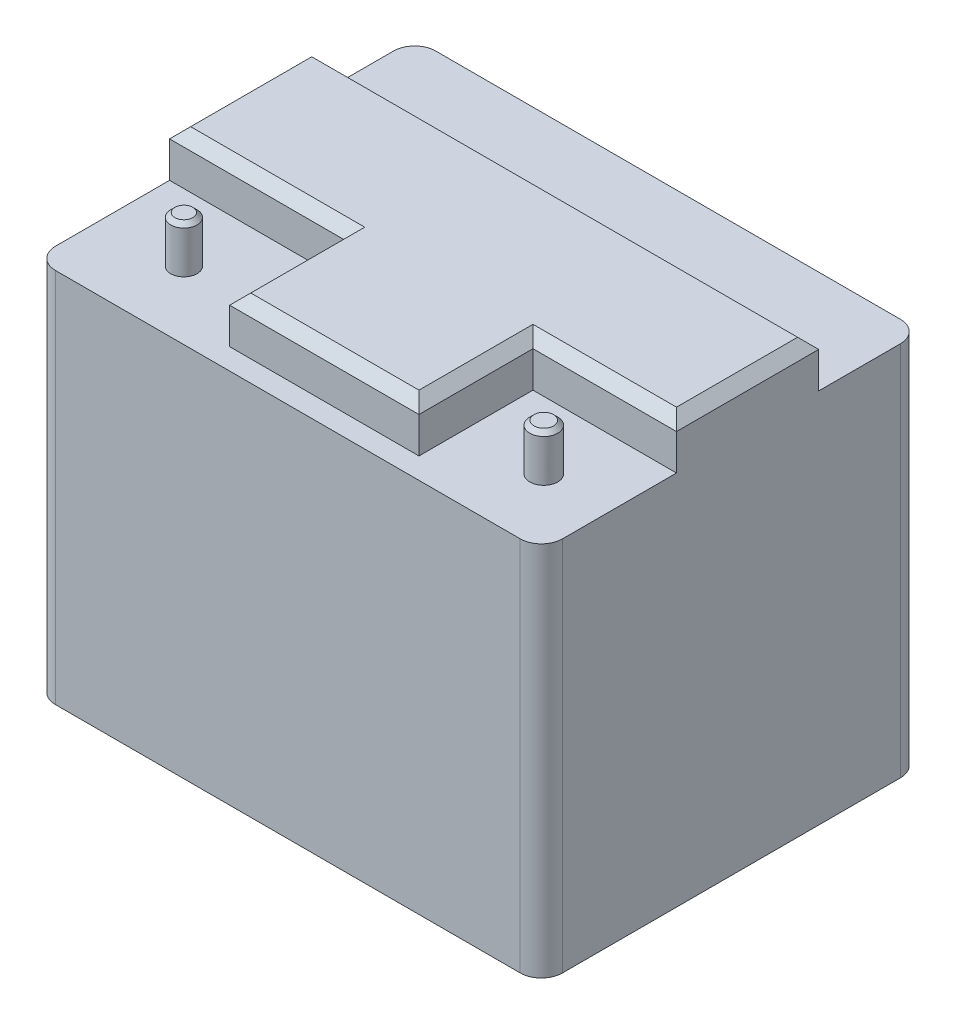
SolidWorks part; units mm, degrees
ref_plane "Alzado" through (0, 0, 0) normal (0, 0, 1) x (1, 0, 0)
ref_plane "Planta" through (0, 0, 0) normal (0, 1, 0) x (1, 0, 0)
ref_plane "Vista lateral" through (0, 0, 0) normal (1, 0, 0) x (0, 0, -1)
sketch "Croquis1" plane through (0, 0, 0) normal (0, 1, 0) x (1, 0, 0)
  line L1 (-110, 90) -> (110, 90)
  line L2 (-120, 80) -> (-120, -80)
  line L3 (-110, -90) -> (110, -90)
  line L4 (120, 80) -> (120, -80)
  line L5 (-120, 90) -> (120, -90) construction
  line L6 (-120, -90) -> (120, 90) construction
  arc A0 (110, 90) -> (120, 80) centre (110, 80) cw
  arc A1 (110, -90) -> (120, -80) centre (110, -80) ccw
  arc A2 (-120, -80) -> (-110, -90) centre (-110, -80) ccw
  arc A3 (-110, 90) -> (-120, 80) centre (-110, 80) ccw
  point P0 (0, 0)
  dimension "D3" = 10
  dimension "D1" = 240
  dimension "D2" = 180
extrude "Saliente-Extruir2" add sketch "Croquis1" along normal blind 200
sketch "Croquis2" plane through (0, 200, 0) normal (0, 1, 0) x (1, 0, 0)
  line L0 (-120, 41.2987) -> (120, 41.2987)
  line L1 (-120, 80) -> (-120, -80) construction
  line L2 (120, -80) -> (120, 80) construction
  line L3 (120, 41.2987) -> (120, -26.0319)
  line L4 (120, -26.0319) -> (-120, -26.0319)
  line L5 (-120, -26.0319) -> (-120, 41.2987)
  line L6 (-37.5799, -26.0319) -> (-37.5799, -80)
  line L7 (-37.5799, -80) -> (52.0638, -80)
  line L8 (52.0638, -80) -> (52.0638, -26.0319)
  line L9 (-110, 90) -> (110, 90)
  line L10 (120, 80) -> (120, -80)
  line L11 (110, -90) -> (-110, -90)
  line L12 (-120, -80) -> (-120, 80)
  circle A0 centre (-81.4245, -57.8134) radius 6.2383
  circle A1 centre (88.9581, -57.8134) radius 6.6282
  arc A2 (110, 90) -> (120, 80) centre (110, 80) cw
  arc A3 (120, -80) -> (110, -90) centre (110, -80) cw
  arc A4 (110, -90) -> (120, -80) centre (110, -80) ccw construction
  arc A5 (-110, -90) -> (-120, -80) centre (-110, -80) cw
  arc A6 (-120, 80) -> (-110, 90) centre (-110, 80) cw
  arc M1 (120, 80) -> (110, 90) centre (110, 80) ccw
  line M2 (110, 90) -> (-110, 90)
  arc M3 (-110, 90) -> (-120, 80) centre (-110, 80) ccw
  line M4 (-120, 80) -> (-120, -80)
  arc M5 (-120, -80) -> (-110, -90) centre (-110, -80) ccw
  line M6 (-110, -90) -> (110, -90)
  arc M7 (110, -90) -> (120, -80) centre (110, -80) ccw
  line M8 (120, -80) -> (120, 80)
extrude "Cortar-Extruir1" cut sketch "Croquis2" against normal blind 22 contours L0 M4 M8 M1 M2 M3 | L8 L7 L6 L4 A1 A0 M4 M5 M6 M7 M8
chamfer "Chaflán1" distance 2 angle 45 2 edges at (88.9581, 200, 64.4416) (-81.4245, 200, 64.0517)
chamfer "Chaflán2" distance 5 angle 45 8 edges at (-37.5799, 200, 53.016) (-78.79, 200, 26.0319) (-120, 200, -7.6334) (0, 200, -41.2987) (120, 200, -7.6334) (86.0319, 200, 26.0319) (52.0638, 200, 53.016) (7.242, 200, 80)
